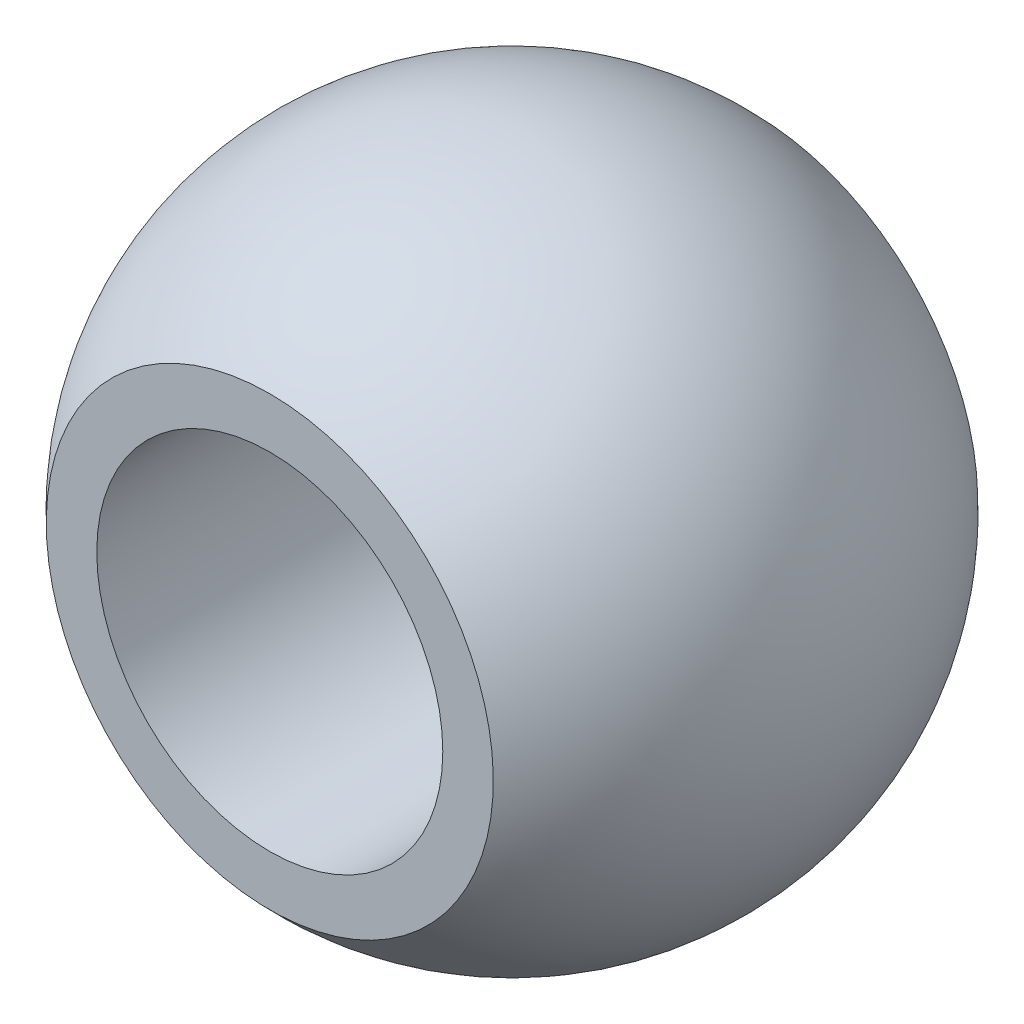
SolidWorks part; units mm, degrees
material "铸造碳钢"
ref_plane "前视基准面" through (0, 0, 0) normal (0, 0, 1) x (1, 0, 0)
ref_plane "上视基准面" through (0, 0, 0) normal (0, 1, 0) x (1, 0, 0)
ref_plane "右视基准面" through (0, 0, 0) normal (1, 0, 0) x (0, 0, -1)
sketch "草图1" plane through (0, 0, 0) normal (1, 0, 0) x (0, 0, -1)
  line L0 (-7, 0) -> (7, 0) construction
  line L1 (-7, 6.4595) -> (-7, 5)
  line L2 (-7, 5) -> (7, 5)
  line L3 (7, 5) -> (7, 6.4595)
  arc A0 (-7, 6.4595) -> (7, 6.4595) centre (0, 0) cw
  point P4 (0, 0)
  point P10 (0, 9.525)
  dimension "B" = 14
  dimension "d" = 10
  dimension "dk" = 19.05
revolve "旋转1" add sketch "草图1" angle 360 about L0
other "冻结***"
